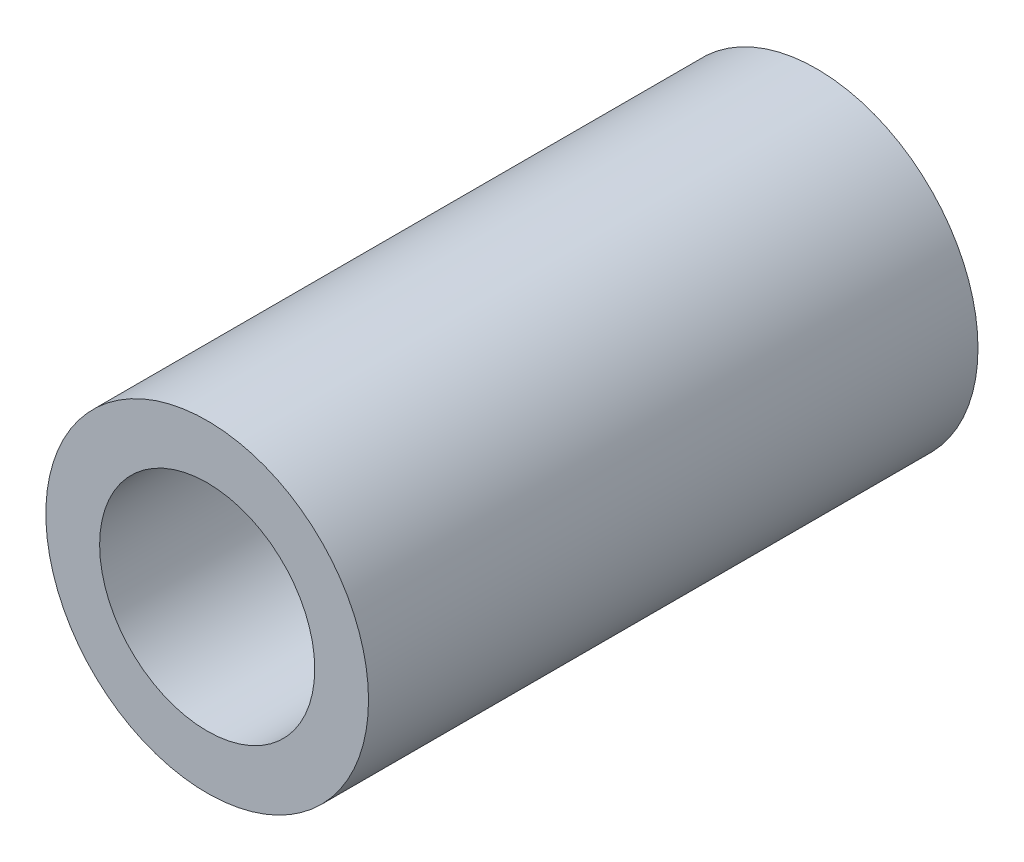
SolidWorks part; units mm, degrees
ref_plane "Płaszczyzna przednia" through (0, 0, 0) normal (0, 0, 1) x (1, 0, 0)
ref_plane "Płaszczyzna górna" through (0, 0, 0) normal (0, 1, 0) x (1, 0, 0)
ref_plane "Płaszczyzna prawa" through (0, 0, 0) normal (1, 0, 0) x (0, 0, -1)
sketch "Sketch1" plane through (0, 0, 0) normal (0, 0, 1) x (1, 0, 0)
  circle A0 centre (0, 0) radius 6
  circle A1 centre (0, 0) radius 9
  dimension "D1" = 3
  dimension "D2" = 12
extrude "Boss-Extrude1" add sketch "Sketch1" along normal mid plane 34
